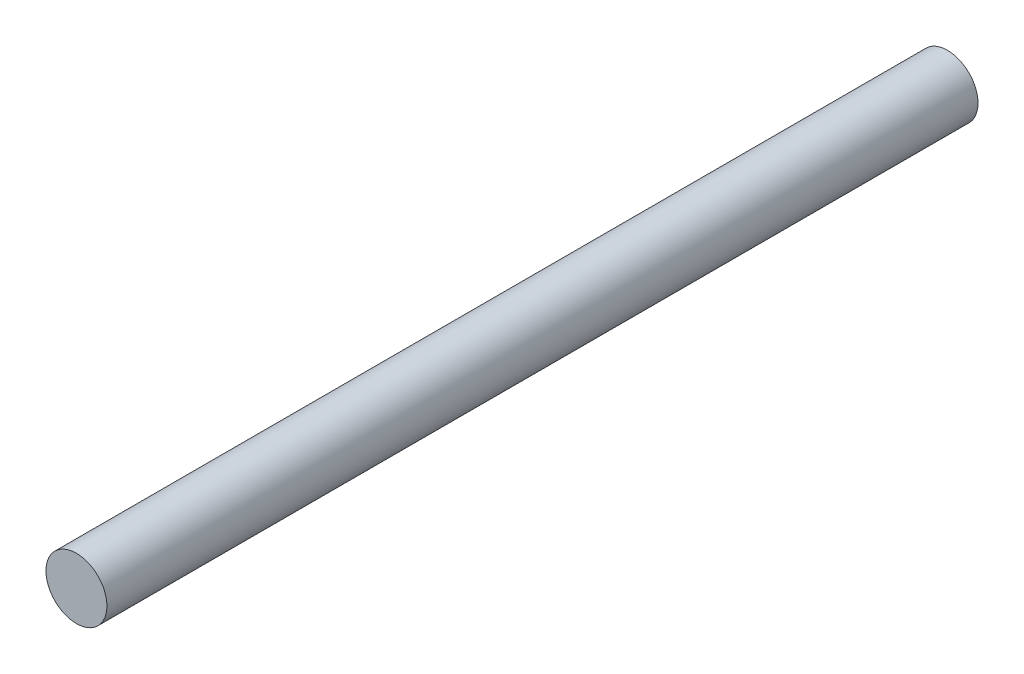
SolidWorks part; units mm, degrees
material "Chrome Stainless Steel"
ref_plane "Front Plane" through (0, 0, 0) normal (0, 0, 1) x (1, 0, 0)
ref_plane "Top Plane" through (0, 0, 0) normal (0, 1, 0) x (1, 0, 0)
ref_plane "Right Plane" through (0, 0, 0) normal (1, 0, 0) x (0, 0, -1)
sketch "Sketch1" plane through (0, 0, 0) normal (0, 0, 1) x (1, 0, 0)
  circle A0 centre (0, 0) radius 9.779
extrude "Boss-Extrude1" add sketch "Sketch1" along normal blind 279.4
